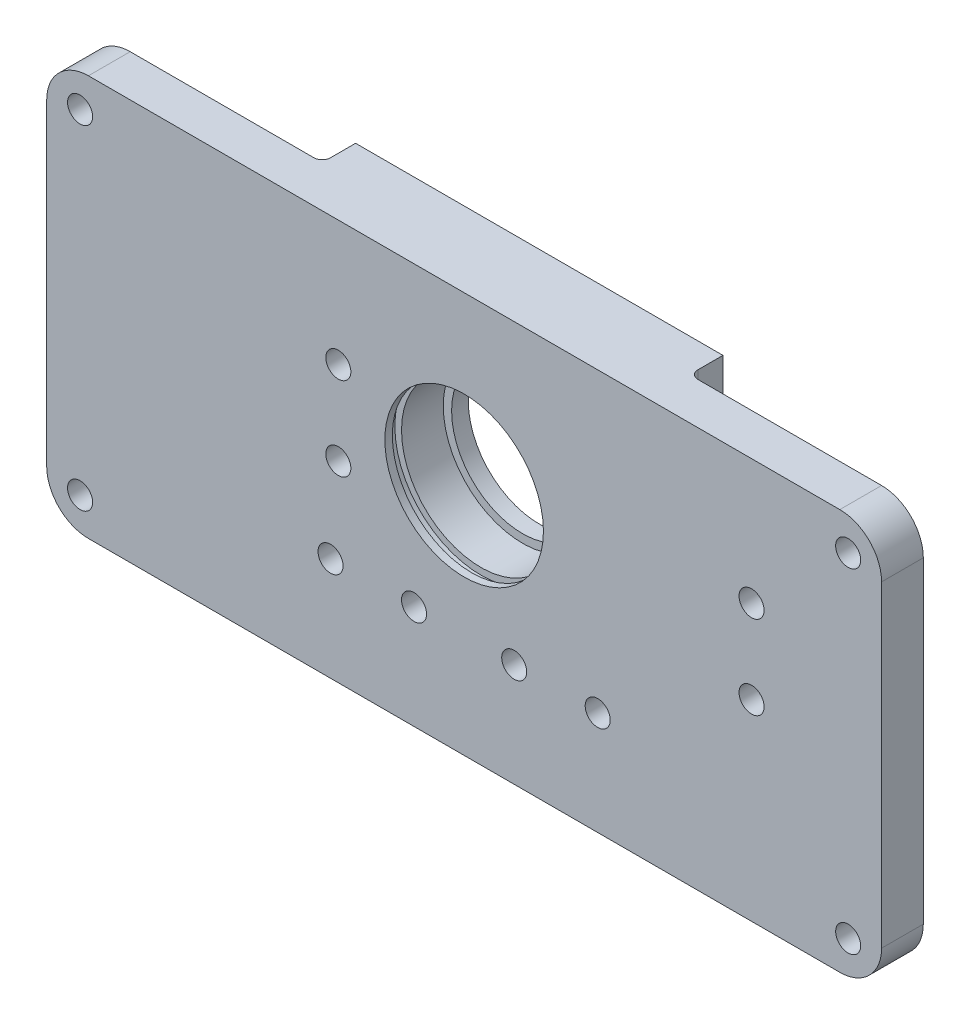
SolidWorks part; units mm, degrees
other "标注1"
sketch "草图12" plane through (-45, 20, 6) normal (-0.9967, 0.0154, 0.0801) x (0.0124, -0.9421, 0.3352)
ref_plane "前视基准面" through (0, 0, 0) normal (0, 0, 1) x (1, 0, 0)
ref_plane "上视基准面" through (0, 0, 0) normal (0, 1, 0) x (1, 0, 0)
ref_plane "右视基准面" through (0, 0, 0) normal (1, 0, 0) x (0, 0, -1)
other "Configuration Table"
sketch "草图1" plane through (0, 0, 0) normal (0, 0, 1) x (1, 0, 0)
  line L1 (-50, 20) -> (50, 20)
  line L2 (-50, 20) -> (-50, -20)
  line L3 (-50, -20) -> (50, -20)
  line L4 (50, 20) -> (50, -20)
  line L5 (-50, 20) -> (50, -20) construction
  line L6 (-50, -20) -> (50, 20) construction
  point P0 (0, 0)
  dimension "D1" = 40
  dimension "D2" = 100
extrude "凸台-拉伸1" add sketch "草图1" along normal blind 6
sketch "草图2" plane through (0, 0, 0) normal (0, 0, -1) x (-1, 0, 0)
  line L1 (-50, 20) -> (50, 20)
  line L2 (-50, 20) -> (-50, -20)
  line L3 (-50, -20) -> (50, -20)
  line L4 (50, 20) -> (50, -20)
  line L5 (-50, 20) -> (50, -20) construction
  line L6 (-50, -20) -> (50, 20) construction
  point P0 (0, 0)
  dimension "D1" = 100
  dimension "D2" = 40
extrude "凸台-拉伸2" add sketch "草图2" along normal blind 3
sketch "草图4" plane through (0, 0, -3) normal (0, 0, -1) x (-1, 0, 0)
  circle A0 centre (0, 0) radius 9.5
  dimension "D1" = 19
extrude "切除-拉伸1" cut sketch "草图4" against normal blind 7
ref_plane "基准面1" through (0, 0, 4) normal (0, 0, -1) x (-1, 0, 0)
sketch "草图5" plane through (0, 0, 4) normal (0, 0, -1) x (-1, 0, 0)
  circle A0 centre (0, 0) radius 10.3
  dimension "D1" = 20.6
extrude "切除-拉伸2" cut sketch "草图5" against normal blind 1.1
sketch "草图6" plane through (0, 0, 6) normal (0, 0, 1) x (1, 0, 0)
  circle A0 centre (0, 0) radius 9.5
  dimension "D1" = 19
extrude "切除-拉伸3" cut sketch "草图6" against normal blind 5
sketch "草图7" plane through (0, 0, 6) normal (0, 0, 1) x (1, 0, 0)
  circle A0 centre (-15.07, 5) radius 1.5
  circle A1 centre (0, 0) radius 9.5 construction
  circle A2 centre (34.43, 5) radius 1.5
  circle A3 centre (-15.07, -5) radius 1.5
  circle A4 centre (34.43, -5) radius 1.5
  dimension "D1" = 3
  dimension "D3" = 5
  dimension "D5" = 2
  dimension "D2" = 15.07
  dimension "D4" = 2
extrude "切除-拉伸4" cut sketch "草图7" against normal blind 12
sketch "草图8" plane through (0, -20, 0) normal (0, -1, 0) x (1, 0, 0)
  line L0 (-50, 6) -> (50, 6) construction
  line L1 (-50, 6) -> (50, 6)
  line L2 (-50, 6) -> (-50, -3)
  line L3 (-50, -3) -> (50, -3)
  line L4 (50, 6) -> (50, -3)
  line L5 (50, -3) -> (-50, -3) construction
  line L6 (-50, 6) -> (-50, -3) construction
  dimension "D1" = 100
  dimension "D2" = 0
extrude "凸台-拉伸3" add sketch "草图8" along normal blind 8
sketch "草图9" plane through (0, 0, -3) normal (0, 0, -1) x (-1, 0, 0)
  line L0 (50, -28) -> (-50, -28) construction
  circle A0 centre (-6, -15.6) radius 1.5
  circle A1 centre (6, -15.6) radius 1.5
  circle A2 centre (-16, -15.6) radius 1.5
  circle A3 centre (16, -15.6) radius 1.5
  dimension "D1" = 3
  dimension "D2" = 12.4
  dimension "D3" = 6
  dimension "D4" = 2
  dimension "D5" = 2
  dimension "D6" = 2
extrude "切除-拉伸5" cut sketch "草图9" against normal blind 10
sketch "草图13" plane through (0, 0, 6) normal (0, 0, 1) x (1, 0, 0)
  line L0 (-50, 20) -> (-50, -28) construction
  line L1 (50, 20) -> (-50, 20) construction
  circle A0 centre (-46, 16) radius 1.5
  circle A1 centre (46, 16) radius 1.5
  circle A4 centre (-46, -24) radius 1.5
  circle A5 centre (46, -24) radius 1.5
  dimension "D1" = 3
  dimension "D2" = 4
  dimension "D3" = 4
  dimension "D4" = 2
  dimension "D6" = 2
extrude "切除-拉伸6" cut sketch "草图13" against normal blind 10
hole_wizard "孔1" positions "3D草图1" profile "草图14" legacy end condition through all
sketch3d "3D草图1"
  line L0 (-16, -15.6, 6) -> (-16, -15.6, -3) construction
  line L1 (-6, -15.6, 6) -> (-6, -15.6, -3) construction
  line L2 (6, -15.6, 6) -> (6, -15.6, -3) construction
  line L3 (16, -15.6, 6) -> (16, -15.6, -3) construction
  point P0 (-16, -15.6, -3)
  point P4 (-6, -15.6, -3)
  point P8 (6, -15.6, -3)
  point P12 (16, -15.6, -3)
sketch "草图14" plane through (-16, -15.6, -3) normal (1, 0, 0) x (0, 1, 0)
  line L0 (0, 0) -> (0, 9)
  line L1 (0, 9) -> (1.5, 9)
  line L2 (1.5, 9) -> (1.5, 3)
  line L3 (1.5, 3) -> (2.75, 3)
  line L4 (2.75, 3) -> (2.75, 0)
  line L5 (2.75, 0) -> (0, 0)
  line L6 (0, 110) -> (0, -10) construction
  dimension "直径" = 3
  dimension "深度" = 9
  dimension "柱坑直径" = 5.5
  dimension "柱坑深度" = 3
sketch "草图15" plane through (0, 0, -3) normal (0, 0, -1) x (-1, 0, 0)
  line L0 (50, -28) -> (50, 20) construction
  line L1 (-50, 24.5962) -> (-22, 24.5962)
  line L2 (-50, 24.5962) -> (-50, -31.8486)
  line L3 (-50, -31.8486) -> (-22, -31.8486)
  line L4 (-22, 24.5962) -> (-22, -31.8486)
  line L5 (50, 23.8486) -> (22, 23.8486)
  line L6 (50, 23.8486) -> (50, -35.0259)
  line L7 (50, -35.0259) -> (22, -35.0259)
  line L8 (22, 23.8486) -> (22, -35.0259)
  line L9 (-50, 20) -> (-50, -28) construction
  dimension "D1" = 28
  dimension "D2" = 28
extrude "切除-拉伸7" cut sketch "草图15" against normal blind 4
fillet "圆角3" radius 1 2 edges at (22, -4, 1) (-22, -4, 1)
fillet "圆角4" radius 5 4 edges at (50, 20, 3.5) (50, -28, 3.5) (-50, -28, 3.5) (-50, 20, 3.5)
sketch "草图16" plane through (0, 0, -3) normal (0, 0, -1) x (-1, 0, 0)
  circle A0 centre (0, 0) radius 9.5
  circle A1 centre (0, 0) radius 8.5
  dimension "D1" = 19
  dimension "D2" = 17
extrude "凸台-拉伸4" add sketch "草图16" against normal blind 2
